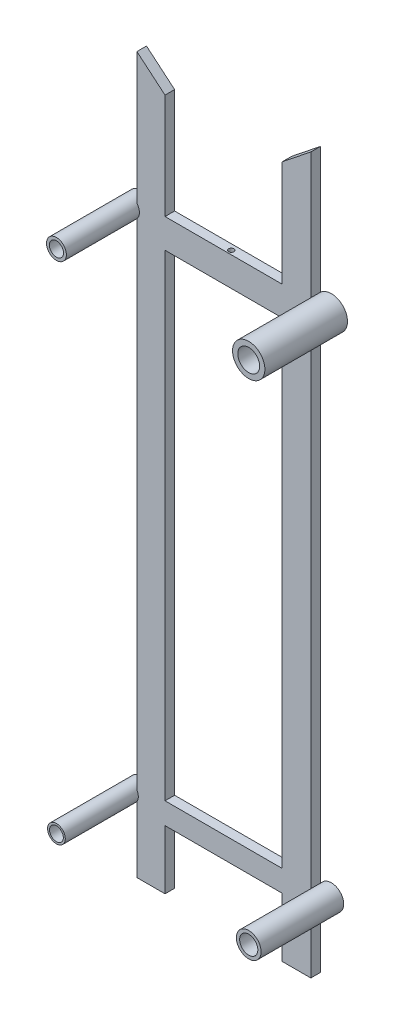
SolidWorks part; units mm, degrees
ref_plane "Front Plane" through (0, 0, 0) normal (0, 0, 1) x (1, 0, 0)
ref_plane "Top Plane" through (0, 0, 0) normal (0, 1, 0) x (1, 0, 0)
ref_plane "Right Plane" through (0, 0, 0) normal (1, 0, 0) x (0, 0, -1)
sketch "Sketch1" plane through (0, 0, 427.0141) normal (0, 0, 1) x (1, 0, 0)
  circle A0 centre (1173.6392, -317.2016) radius 38.7717
  circle A1 centre (1173.6392, -317.2016) radius 57.281
  circle A2 centre (491.7651, -317.2016) radius 25.1474
  circle A3 centre (491.7651, -317.2016) radius 35.2569
  circle A4 centre (491.7651, -2112.8608) radius 24.5211
  circle A5 centre (491.7651, -2112.8608) radius 31.4285
  circle A6 centre (1173.6392, -2112.8608) radius 32.2545
  circle A7 centre (1173.6392, -2112.8608) radius 43.7966
extrude "Boss-Extrude1" add sketch "Sketch1" along normal blind 293 from offset 600
sketch "Sketch2" plane through (0, 0, 1027.0141) normal (0, 0, -1) x (-1, 0, 0)
  line L0 (-1134.8675, 91.6172) -> (-1134.8675, 172.7652)
  line L1 (-1134.8675, -2363.9974) -> (-1033.1667, -2363.9974)
  line L2 (-1134.8675, -2363.9974) -> (-1134.8675, 91.6172)
  line L4 (-1033.1667, -2363.9974) -> (-1033.1667, 91.6172)
  line L5 (-518.1595, -2363.9974) -> (-617.8837, -2363.9974)
  line L6 (-518.1595, -2363.9974) -> (-518.1595, 88.9058)
  line L8 (-617.8837, -2363.9974) -> (-617.8837, 88.9058)
  line L9 (-1134.8675, -2154.5063) -> (-518.1595, -2154.5063)
  line L10 (-1134.8675, -2154.5063) -> (-1134.8675, -2078.311)
  line L11 (-1134.8675, -2078.311) -> (-518.1595, -2078.311)
  line L12 (-518.1595, -2154.5063) -> (-518.1595, -2078.311)
  line L13 (-1134.8675, -387.5825) -> (-518.1595, -387.5825)
  line L14 (-1134.8675, -387.5825) -> (-1134.8675, -284.0952)
  line L15 (-1134.8675, -284.0952) -> (-518.1595, -284.0952)
  line L16 (-518.1595, -387.5825) -> (-518.1595, -284.0952)
  line L17 (-1134.8675, 769) -> (-1134.8675, -2363.9974) construction
  line L18 (-1134.8675, 172.7652) -> (-1033.1667, 91.6172)
  line L19 (-518.1595, 88.9058) -> (-518.1595, 172.7652)
  line L20 (-518.1595, 769) -> (-518.1595, -2363.9974) construction
  line L21 (-518.1595, 172.7652) -> (-617.8837, 88.9058)
  circle A0 centre (-833.9306, -1197.1664) radius 1304.0928 construction
extrude "Boss-Extrude2" add sketch "Sketch2" against normal blind 34
sketch "Sketch6" plane through (0, -284.0952, 0) normal (0, 1, 0) x (1, 0, 0)
  circle A0 centre (838.8984, -1047.1552) radius 9.3137
extrude "Cut-Extrude3" cut sketch "Sketch6" against normal blind 126
